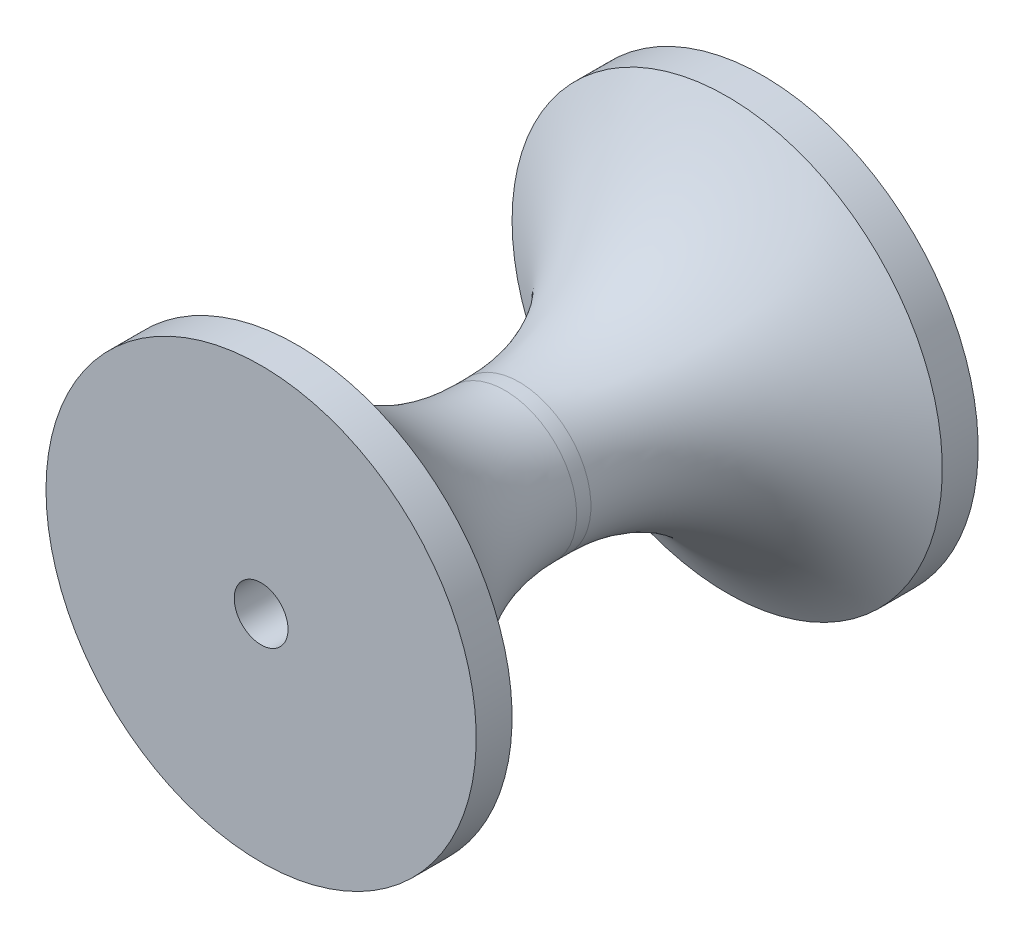
SolidWorks part; units mm, degrees
material "ABS"
ref_plane "Front Plane" through (0, 0, 0) normal (0, 0, 1) x (1, 0, 0)
ref_plane "Top Plane" through (0, 0, 0) normal (0, 1, 0) x (1, 0, 0)
ref_plane "Right Plane" through (0, 0, 0) normal (1, 0, 0) x (0, 0, -1)
sketch "Sketch1" plane through (0, 0, 0) normal (1, 0, 0) x (0, 0, -1)
  line L0 (0, 0) -> (0, 12.7)
  line L3 (51.2368, 0) -> (-51.2368, 0) construction
  line L4 (38.1, 38.1) -> (44.45, 38.1)
  line L5 (44.45, 38.1) -> (44.45, 0)
  line L7 (0, 12.7) -> (1.27, 12.7)
  line L8 (0, 0) -> (44.45, 0)
  spline S0 degree 2 poles (1.27, 12.7) (23.6397, 12.7) (38.1, 38.1) knots 0 0 0 1 1 1
  point P8 (0, 0)
  dimension "D5" = 1.27
  dimension "D6" = 47.0718
  dimension "D1" = 12.7
  dimension "D2" = 44.45
  dimension "D3" = 38.1
  dimension "D4" = 6.35
revolve "Revolve1" add sketch "Sketch1" angle 360 about L3
mirror "Mirror1" about plane through (0, 0, 0) normal (0, 0, 1) of "Revolve1"
sketch "Sketch2" plane through (0, 0, 0) normal (0, 0, 1) x (1, 0, 0)
  circle A0 centre (0, 0) radius 4.7625
  dimension "D1" = 9.525
extrude "Cut-Extrude1" cut sketch "Sketch2" against normal through all both and the other way through all
